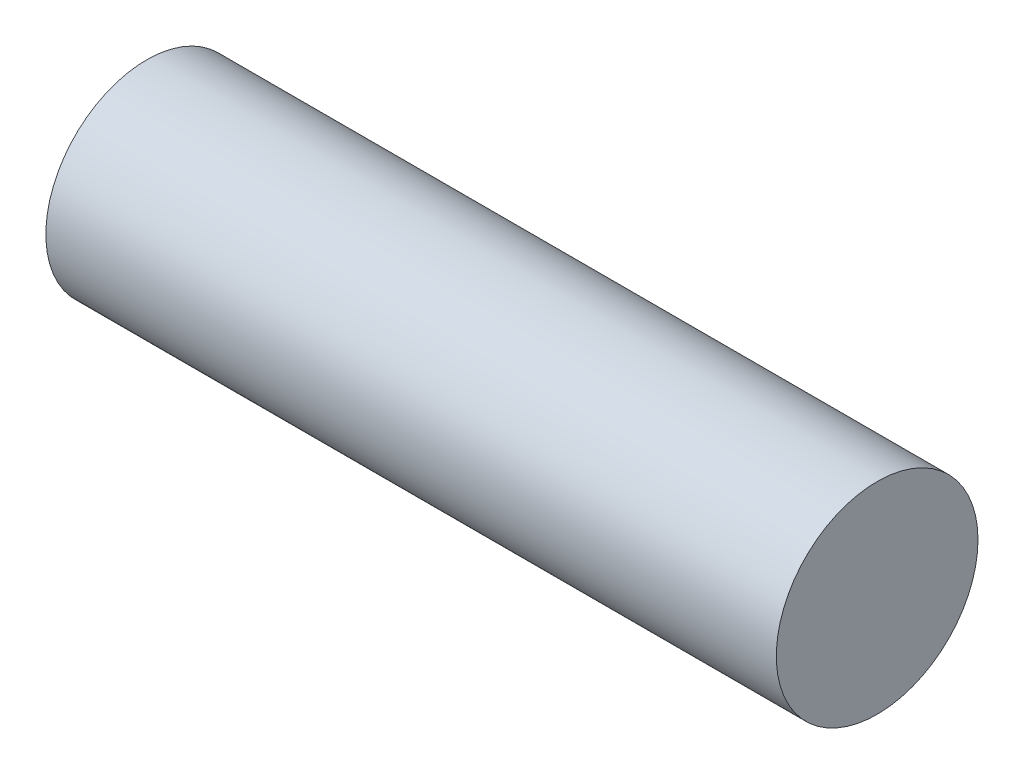
SolidWorks part; units mm, degrees
ref_plane "Plano frontal" through (0, 0, 0) normal (0, 0, 1) x (1, 0, 0)
ref_plane "Plano superior" through (0, 0, 0) normal (0, 1, 0) x (1, 0, 0)
ref_plane "Plano direito" through (0, 0, 0) normal (1, 0, 0) x (0, 0, -1)
sketch "Esboço1" plane through (0, 0, 0) normal (1, 0, 0) x (0, 0, -1)
  circle A0 centre (0, 0) radius 9.25
  dimension "D1" = 18.5
extrude "Ressalto-extrusão1" add sketch "Esboço1" against normal blind 67
